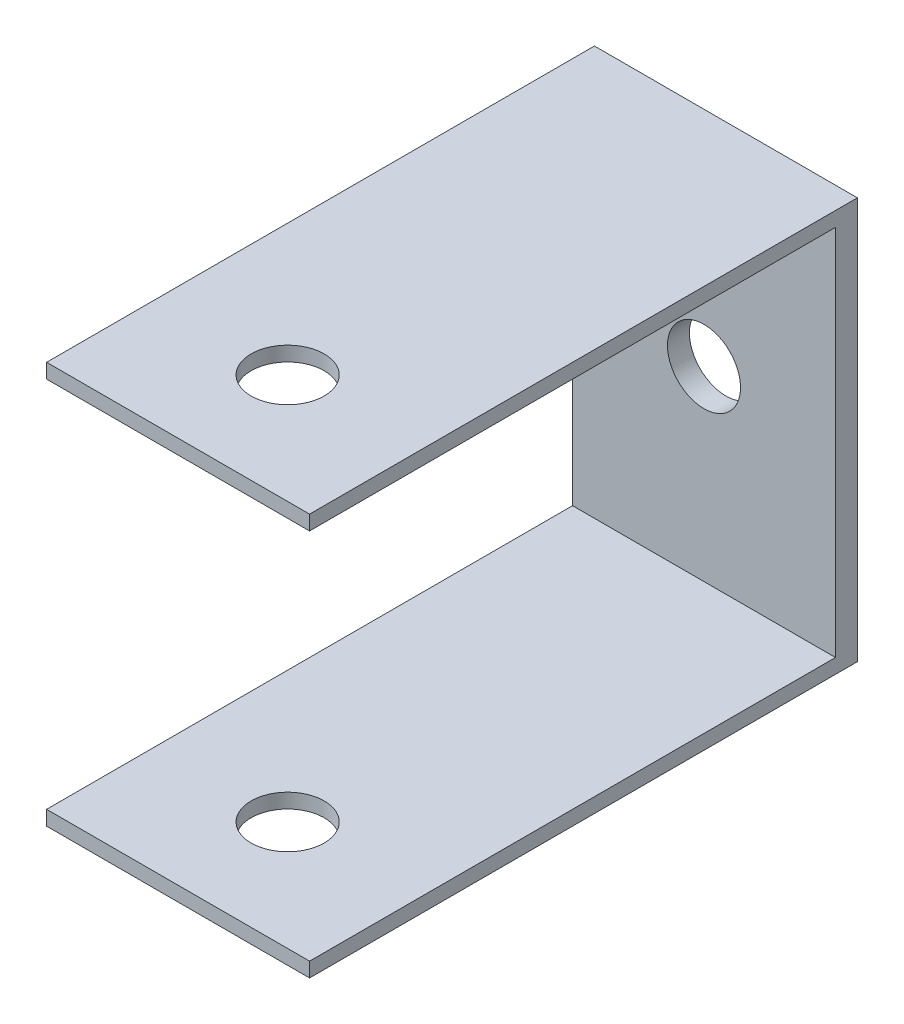
SolidWorks part; units mm, degrees
ref_plane "Plano frontal" through (0, 0, 0) normal (0, 0, 1) x (1, 0, 0)
ref_plane "Plano superior" through (0, 0, 0) normal (0, 1, 0) x (1, 0, 0)
ref_plane "Plano direito" through (0, 0, 0) normal (1, 0, 0) x (0, 0, -1)
sketch "Esboço1" plane through (0, 0, 0) normal (0, 0, 1) x (1, 0, 0)
  line L1 (18, 27.5) -> (-18, 27.5)
  line L2 (18, 27.5) -> (18, -27.5)
  line L3 (18, -27.5) -> (-18, -27.5)
  line L4 (-18, 27.5) -> (-18, -27.5)
  line L5 (18, 27.5) -> (-18, -27.5) construction
  line L6 (18, -27.5) -> (-18, 27.5) construction
  point P0 (0, 0)
  dimension "D1" = 36
  dimension "D2" = 55
extrude "Ressalto-extrusão1" add sketch "Esboço1" along normal blind 75
sketch "Esboço2" plane through (0, 0, 75) normal (0, 0, 1) x (1, 0, 0)
  line L1 (17, 15) -> (-17, 15)
  line L2 (17, 15) -> (17, -15)
  line L3 (17, -15) -> (-17, -15)
  line L4 (-17, 15) -> (-17, -15)
  line L5 (17, 15) -> (-17, -15) construction
  line L6 (17, -15) -> (-17, 15) construction
  point P0 (0, 0)
  dimension "D1" = 34
  dimension "D2" = 30
extrude "Corte-extrusão1" cut sketch "Esboço2" against normal blind 56
sketch "Esboço3" plane through (-18, 0, 0) normal (-1, 0, 0) x (0, 0, 1)
  line L0 (75, 27.5) -> (75, -27.5) construction
  line L1 (19, -25.5) -> (75, -25.5)
  line L2 (19, -25.5) -> (19, 25.5)
  line L3 (19, 25.5) -> (75, 25.5)
  line L4 (75, -25.5) -> (75, 25.5)
  line L5 (19, -25.5) -> (75, 25.5) construction
  line L6 (19, 25.5) -> (75, -25.5) construction
  line L7 (75, -27.5) -> (0, -27.5) construction
  line L8 (75, 27.5) -> (0, 27.5) construction
  point P0 (47, 0)
  dimension "D1" = 56
  dimension "D2" = 2
  dimension "D3" = 2
extrude "Corte-extrusão2" cut sketch "Esboço3" against normal blind 57
sketch "Esboço4" plane through (0, -27.5, 0) normal (0, -1, 0) x (1, 0, 0)
  line L0 (-18, 75) -> (18, 75) construction
  circle A0 centre (0, 60) radius 5
  dimension "D1" = 10
  dimension "D2" = 15
sketch "Esboço5" plane through (0, 0, 0) normal (0, 0, -1) x (-1, 0, 0)
  circle A0 centre (0, 0) radius 5
  dimension "D1" = 10
extrude "Corte-extrusão4" cut sketch "Esboço5" against normal blind 57
sketch "Esboço6" plane through (0, 0, 19) normal (0, 0, 1) x (1, 0, 0)
  line L0 (18, 25.5) -> (18, -25.5) construction
  line L1 (-18, 25.5) -> (18, 25.5)
  line L2 (-18, 25.5) -> (-18, -25.5)
  line L3 (-18, -25.5) -> (18, -25.5)
  line L4 (18, 25.5) -> (18, -25.5)
extrude "Corte-extrusão5" cut sketch "Esboço6" against normal blind 16
extrude "Corte-extrusão6" cut sketch "Esboço4" against normal blind 63
